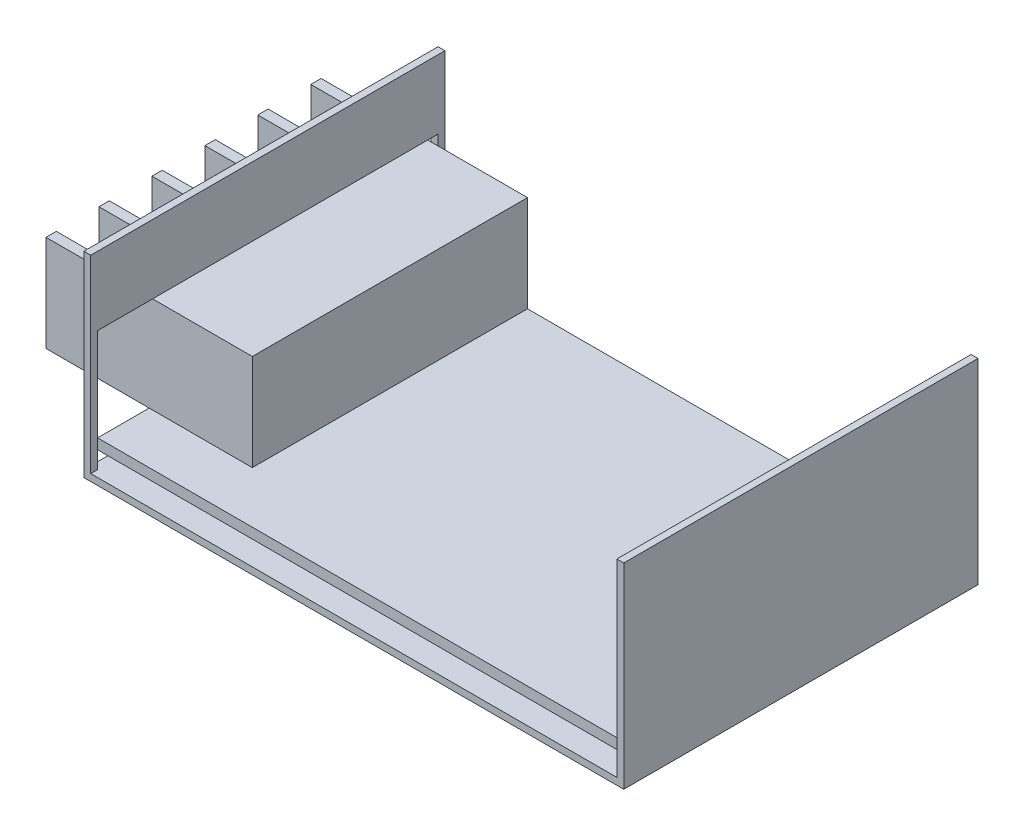
SolidWorks part; units mm, degrees
ref_plane "Спереди" through (0, 0, 0) normal (0, 0, 1) x (1, 0, 0)
ref_plane "Сверху" through (0, 0, 0) normal (0, 1, 0) x (1, 0, 0)
ref_plane "Справа" through (0, 0, 0) normal (1, 0, 0) x (0, 0, -1)
sketch "Эскиз1" plane through (0, 0, 0) normal (0, 0, 1) x (1, 0, 0)
  line L0 (1, 1) -> (77.5, 1)
  line L1 (77.5, 1) -> (77.5, 28.5)
  line L2 (1, 28.5) -> (1, 1)
  line L3 (0, 0) -> (78.5, 0)
  line L4 (78.5, 0) -> (78.5, 28.5)
  line L5 (78.5, 28.5) -> (77.5, 28.5)
  line L6 (0, 28.5) -> (0, 0)
  line L7 (1, 28.5) -> (0, 28.5)
extrude "Бобышка-Вытянуть1" add sketch "Эскиз1" along normal blind 51.5
sketch "Эскиз2" plane through (0, 0, 0) normal (-1, 0, 0) x (0, 0, 1)
  line L0 (1, 18.5) -> (50.5, 18.5)
  line L7 (50.5, 18.5) -> (50.5, 1)
  line L8 (1, 1) -> (50.5, 1)
  line L9 (1, 1) -> (1, 18.5)
extrude "Вырез-Вытянуть1" cut sketch "Эскиз2" against normal blind 10
sketch "Эскиз3" plane through (77.5, 0, 0) normal (-1, 0, 0) x (0, 0, 1)
  line L6 (2, 2.5) -> (49.5, 2.5)
  line L7 (49.5, 2.5) -> (49.5, 4)
  line L8 (49.5, 4) -> (2, 4)
  line L9 (2, 4) -> (2, 2.5)
extrude "Бобышка-Вытянуть2" add sketch "Эскиз3" along normal up to surface (77.5 mm away) up to face at (0, 9.75, 25.75)
sketch "Эскиз4" plane through (0, 4, 0) normal (0, 1, 0) x (1, 0, 0)
  line L0 (-15, -2) -> (15, -2)
  line L1 (0, -2) -> (77.5, -2) construction
  line L2 (15, -2) -> (15, -42)
  line L3 (15, -42) -> (-15, -42)
  line L4 (-15, -42) -> (-15, -2)
extrude "Бобышка-Вытянуть3" add sketch "Эскиз4" along normal blind 14
sketch "Эскиз5" plane through (0, 18, 0) normal (0, 1, 0) x (1, 0, 0)
  line L0 (-7, -3.5) -> (-15, -3.5)
  line L1 (-7, -34.3) -> (-7, -40.5)
  line L2 (-7, -9.7) -> (-15, -9.7)
  line L3 (-15, -11.2) -> (-7, -11.2)
  line L4 (-15, -34.3) -> (-15, -40.5)
  line L5 (-15, -17.4) -> (-7, -17.4)
  line L6 (-7, -18.9) -> (-15, -18.9)
  line L7 (-15, -26.6) -> (-15, -32.8)
  line L8 (-15, -25.1) -> (-7, -25.1)
  line L9 (-7, -26.6) -> (-15, -26.6)
  line L10 (-7, -26.6) -> (-7, -32.8)
  line L11 (-7, -32.8) -> (-15, -32.8)
  line L12 (-15, -34.3) -> (-7, -34.3)
  line L13 (-15, -18.9) -> (-15, -25.1)
  line L14 (-15, -40.5) -> (-7, -40.5)
  line L15 (-7, -18.9) -> (-7, -25.1)
  line L16 (-15, -11.2) -> (-15, -17.4)
  line L17 (-7, -11.2) -> (-7, -17.4)
  line L18 (-15, -3.5) -> (-15, -9.7)
  line L19 (-7, -3.5) -> (-7, -9.7)
extrude "Вырез-Вытянуть2" cut sketch "Эскиз5" against normal blind 24
chamfer "Фаска1" distance 2 angle 45 10 edges at (-7, 4, 6.6) (-7, 4, 14.3) (-7, 4, 22) (-7, 4, 29.7) (-7, 4, 37.4) (-7, 18, 37.4) (-7, 18, 29.7) (-7, 18, 22) (-7, 18, 14.3) (-7, 18, 6.6)
hole_wizard "Отверстие обработанное метчиком M31" positions "Эскиз6" profile "Эскиз7" tap size "M3" standard "ISO"
sketch "Эскиз6" plane through (0, 0, 0) normal (0, -1, 0) x (-1, 0, 0)
  line L0 (-78.5, -51.5) -> (-78.5, 0) construction
  line L1 (0, -51.5) -> (-78.5, -51.5) construction
  point P0 (-13, -25.4)
  point P2 (-68, -25.4)
  dimension "D1" = 55
  dimension "D2" = 0
  dimension "D3" = 10.5
  dimension "D4" = 26.1
sketch "Эскиз7" plane through (13, 0, 25.4) normal (1, 0, 0) x (0, 0, -1)
  line L0 (0, 0) -> (0, 9.2511)
  line L1 (0, 9.2511) -> (1.25, 8.5)
  line L2 (1.25, 8.5) -> (1.25, 0)
  line L5 (1.25, 0) -> (0, 0)
  line L10 (0, 9.2511) -> (-1.25, 8.5) construction
  line L11 (0, -6.35) -> (0, 107.95) construction
  dimension "Диаметр сверла" = 2.5
  dimension "Глубина сверла" = 8.5
  dimension "Угол заточки сверла" = 118
cosmetic thread "Отверстие резьбы1" parameters "D1"=4, "D2"=3
cosmetic thread "Отверстие резьбы2" parameters "D1"=6, "D2"=3
